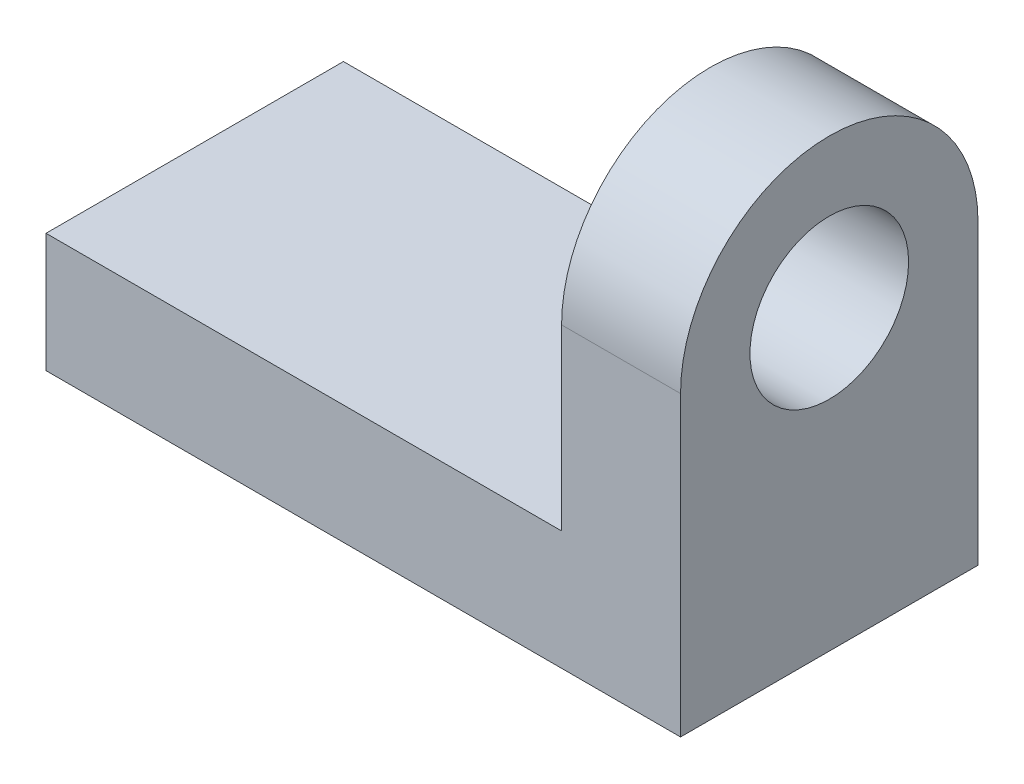
SolidWorks part; units mm, degrees
ref_plane "Alzado" through (0, 0, 0) normal (0, 0, 1) x (1, 0, 0)
ref_plane "Planta" through (0, 0, 0) normal (0, 1, 0) x (1, 0, 0)
ref_plane "Vista lateral" through (0, 0, 0) normal (1, 0, 0) x (0, 0, -1)
sketch "Croquis1" plane through (0, 0, 0) normal (0, 1, 0) x (1, 0, 0)
  line L1 (65, 37.5) -> (-65, 37.5)
  line L2 (65, 37.5) -> (65, -37.5)
  line L3 (65, -37.5) -> (-65, -37.5)
  line L4 (-65, 37.5) -> (-65, -37.5)
  line L5 (65, 37.5) -> (-65, -37.5) construction
  line L6 (65, -37.5) -> (-65, 37.5) construction
  point P0 (0, 0)
  dimension "D1" = 130
  dimension "D2" = 75
extrude "Saliente-Extruir1" add sketch "Croquis1" along normal blind 30
sketch "Croquis2" plane through (65, 0, 0) normal (1, 0, 0) x (0, 0, -1)
  line L0 (37.5, 30) -> (37.5, 0) construction
  line L1 (-37.5, 0) -> (37.5, 0)
  line L2 (-37.5, 0) -> (-37.5, 75)
  line L4 (37.5, 0) -> (37.5, 75)
  arc A0 (37.5, 75) -> (-37.5, 75) centre (0, 75) ccw
  dimension "D1" = 75
extrude "Saliente-Extruir2" add sketch "Croquis2" along normal blind 30
sketch "Croquis3" plane through (95, 0, 0) normal (1, 0, 0) x (0, 0, -1)
  circle A0 centre (0, 75) radius 20
  dimension "D1" = 40
extrude "Cortar-Extruir1" cut sketch "Croquis3" against normal blind 62
ref_plane "Plano2" through (0, 33.75, -33.75) normal (0, 0.7071, -0.7071) x (1, 0, 0)
sketch "Croquis4" plane through (0, 33.75, -33.75) normal (0, 0.7071, -0.7071) x (1, 0, 0)
  line L1 (-65, 5.3033) -> (5, 5.3033)
  line L2 (-65, 5.3033) -> (-65, -34.6967)
  line L3 (-65, -34.6967) -> (5, -34.6967)
  arc A1 (5, 5.3033) -> (5, -34.6967) centre (5, -14.6967) cw
  dimension "D2" = 40
  dimension "D4" = 20
  dimension "D1" = 70
  dimension "D3" = 70
